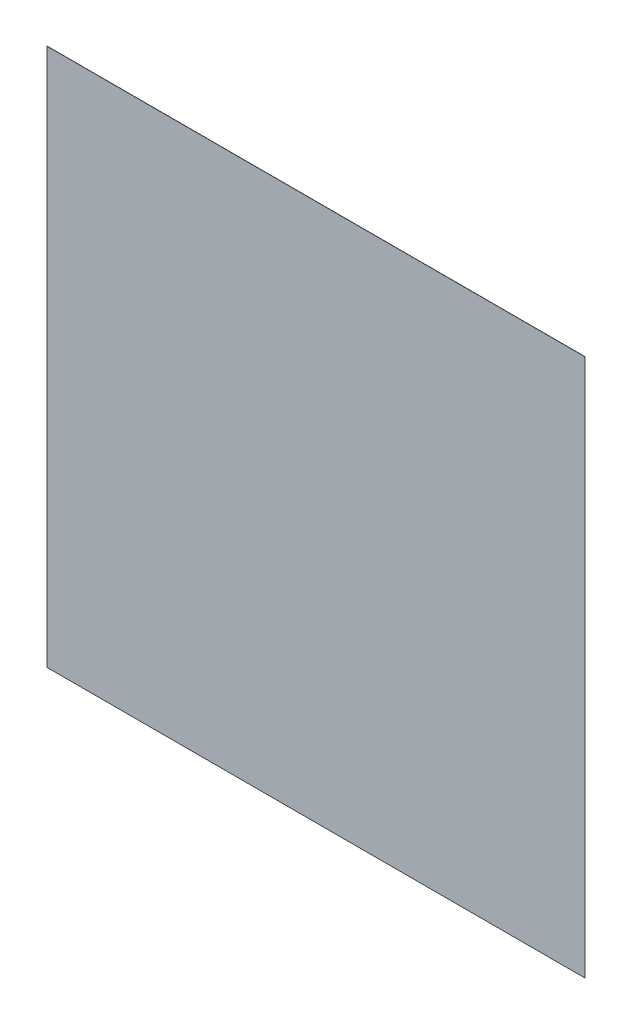
SolidWorks part; units mm, degrees
ref_plane "Front Plane" through (0, 0, 0) normal (0, 0, 1) x (1, 0, 0)
ref_plane "Top Plane" through (0, 0, 0) normal (0, 1, 0) x (1, 0, 0)
ref_plane "Right Plane" through (0, 0, 0) normal (1, 0, 0) x (0, 0, -1)
sketch "Sketch1" plane through (0, 0, 0) normal (0, 0, 1) x (1, 0, 0)
  line L0 (0, 150) -> (0, -150) construction
  line L1 (-150, 150) -> (150, 150)
  line L2 (-150, 150) -> (-150, -150)
  line L3 (-150, -150) -> (150, -150)
  line L4 (150, 150) -> (150, -150)
  dimension "D1" = 300
extrude "Boss-Extrude1" add sketch "Sketch1" along normal blind 0.1
